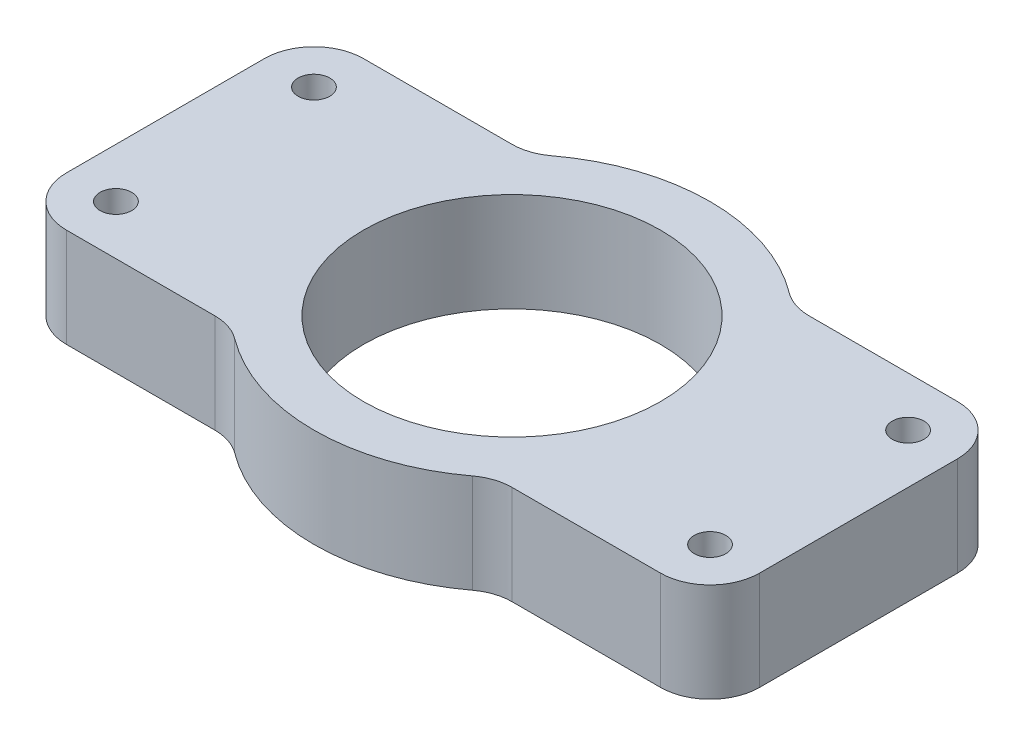
SolidWorks part; units mm, degrees
material "Acrylic (Medium-high impact)"
ref_plane "Front Plane" through (0, 0, 0) normal (0, 0, 1) x (1, 0, 0)
ref_plane "Top Plane" through (0, 0, 0) normal (0, 1, 0) x (1, 0, 0)
ref_plane "Right Plane" through (0, 0, 0) normal (1, 0, 0) x (0, 0, -1)
sketch "Sketch1" plane through (0, 0, 0) normal (0, 1, 0) x (1, 0, 0)
  line L1 (-35, -15) -> (35, -15)
  line L2 (-35, -15) -> (-35, 15)
  line L3 (-35, 15) -> (35, 15)
  line L4 (35, -15) -> (35, 15)
  line L5 (-35, -15) -> (35, 15) construction
  line L6 (-35, 15) -> (35, -15) construction
  point P0 (0, 0)
  dimension "D1" = 30
  dimension "D2" = 70
extrude "Boss-Extrude1" add sketch "Sketch1" along normal blind 10
sketch "Sketch2" plane through (0, 0, 0) normal (0, 1, 0) x (1, 0, 0)
  circle A0 centre (0, 0) radius 20
  dimension "D1" = 40
extrude "Boss-Extrude2" add sketch "Sketch2" along normal blind 10
sketch "Sketch3" plane through (0, 10, 0) normal (0, 1, 0) x (1, 0, 0)
  circle A0 centre (0, 0) radius 15
  dimension "D1" = 30
extrude "Cut-Extrude1" cut sketch "Sketch3" against normal through all both and the other way through all
sketch "Sketch4" plane through (0, 10, 0) normal (0, 1, 0) x (1, 0, 0)
  line L1 (-30, -10) -> (30, -10) construction
  line L2 (-30, -10) -> (-30, 10) construction
  line L3 (-30, 10) -> (30, 10) construction
  line L4 (30, -10) -> (30, 10) construction
  line L5 (-30, -10) -> (30, 10) construction
  line L6 (-30, 10) -> (30, -10) construction
  circle A0 centre (-30, 10) radius 1.6
  circle A1 centre (30, -10) radius 1.6
  circle A2 centre (30, 10) radius 1.6
  circle A3 centre (-30, -10) radius 1.6
  point P0 (0, 0)
  dimension "D3" = 3.2
  dimension "D1" = 60
  dimension "D2" = 20
extrude "Cut-Extrude2" cut sketch "Sketch4" against normal through all both and the other way through all
fillet "Fillet1" radius 5 8 edges at (-13.2288, 5, -15) (13.2288, 5, -15) (-35, 5, -15) (-35, 5, 15) (13.2288, 5, 15) (-13.2288, 5, 15) (35, 5, -15) (35, 5, 15)
